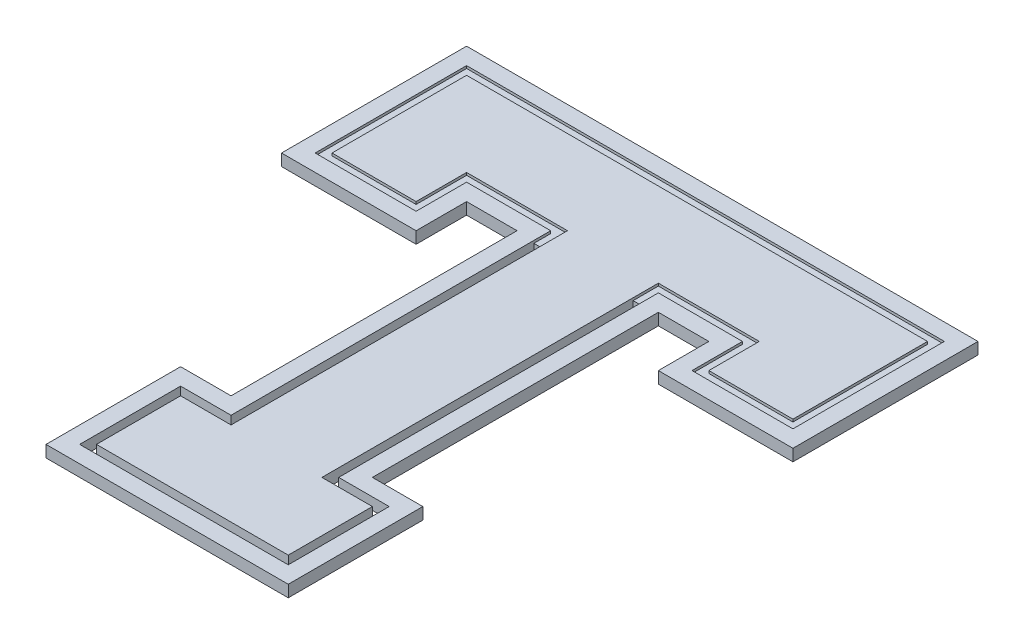
SolidWorks part; units mm, degrees
ref_plane "Front Plane" through (0, 0, 0) normal (0, 0, 1) x (1, 0, 0)
ref_plane "Top Plane" through (0, 0, 0) normal (0, 1, 0) x (1, 0, 0)
ref_plane "Right Plane" through (0, 0, 0) normal (1, 0, 0) x (0, 0, -1)
sketch "Sketch1" plane through (0, 0, 0) normal (0, 1, 0) x (1, 0, 0)
  line L0 (64.3712, 193.1137) -> (321.8562, 193.1137) construction
  line L1 (-20.32, 83.82) -> (-20.32, 55.88)
  line L2 (-20.32, 55.88) -> (0, 55.88)
  line L3 (0, 55.88) -> (0, 63.5)
  line L4 (0, 63.5) -> (7.62, 63.5)
  line L5 (7.62, 63.5) -> (7.62, 20.32)
  line L6 (7.62, 20.32) -> (0, 20.32)
  line L7 (0, 20.32) -> (0, 0)
  line L8 (0, 0) -> (36.576, 0)
  line L9 (36.576, 0) -> (36.576, 20.32)
  line L11 (36.576, 20.32) -> (28.956, 20.32)
  line L12 (28.956, 20.32) -> (28.956, 63.5)
  line L13 (28.956, 63.5) -> (36.576, 63.5)
  line L14 (36.576, 63.5) -> (36.576, 55.88)
  line L15 (36.576, 55.88) -> (56.896, 55.88)
  line L16 (56.896, 55.88) -> (56.896, 83.82)
  line L17 (56.896, 83.82) -> (-20.32, 83.82)
  line L19 (10.16, 17.78) -> (2.54, 17.78)
  line L20 (2.54, 17.78) -> (2.54, 2.54)
  line L21 (2.54, 2.54) -> (34.036, 2.54)
  line L22 (34.036, 2.54) -> (34.036, 17.78)
  line L23 (34.036, 17.78) -> (26.416, 17.78)
  line L24 (26.416, 17.78) -> (26.416, 63.5)
  line L35 (11.43, 16.51) -> (3.81, 16.51)
  line L36 (3.81, 16.51) -> (3.81, 3.81)
  line L37 (3.81, 3.81) -> (32.766, 3.81)
  line L38 (32.766, 3.81) -> (32.766, 16.51)
  line L39 (32.766, 16.51) -> (25.146, 16.51)
  line L40 (25.146, 16.51) -> (25.146, 63.5)
  line L50 (10.16, 63.5) -> (11.43, 63.5)
  line L51 (26.416, 63.5) -> (25.146, 63.5)
  line L52 (11.43, 63.5) -> (11.43, 16.51)
  line L53 (11.43, 67.31) -> (11.43, 16.51) construction
  line L54 (10.16, 63.5) -> (10.16, 17.78)
  line L55 (10.16, 66.04) -> (10.16, 17.78) construction
  line L57 (25.146, 16.51) -> (25.146, 67.31) construction
  line L59 (26.416, 17.78) -> (26.416, 66.04) construction
  line L60 (-17.78, 81.28) -> (-17.78, 58.42) construction
  line L61 (-16.51, 80.01) -> (-16.51, 59.69) construction
  line L62 (-17.78, 58.42) -> (-2.54, 58.42) construction
  line L63 (-16.51, 59.69) -> (-3.81, 59.69) construction
  line L64 (-2.54, 58.42) -> (-2.54, 66.04) construction
  line L65 (-3.81, 59.69) -> (-3.81, 67.31) construction
  line L66 (-3.81, 67.31) -> (11.43, 67.31) construction
  line L67 (-2.54, 66.04) -> (10.16, 66.04) construction
  line L68 (26.416, 66.04) -> (39.116, 66.04) construction
  line L69 (25.146, 67.31) -> (40.386, 67.31) construction
  line L70 (39.116, 66.04) -> (39.116, 58.42) construction
  line L71 (40.386, 67.31) -> (40.386, 59.69) construction
  line L72 (40.386, 59.69) -> (53.086, 59.69) construction
  line L73 (39.116, 58.42) -> (54.356, 58.42) construction
  line L74 (53.086, 59.69) -> (53.086, 80.01) construction
  line L75 (54.356, 58.42) -> (54.356, 81.28) construction
  line L76 (54.356, 81.28) -> (-17.78, 81.28) construction
  line L77 (53.086, 80.01) -> (-16.51, 80.01) construction
  point P54 (-6.6893, 80.4636)
  dimension "D1" = 27.94
  dimension "D2" = 20.32
  dimension "D3" = 20.32
  dimension "D4" = 7.62
  dimension "D5" = 7.62
  dimension "D6" = 7.62
  dimension "D7" = 7.62
  dimension "D8" = 27.94
  dimension "D9" = 43.18
  dimension "D10" = 43.18
  dimension "D11" = 7.62
  dimension "D12" = 20.32
  dimension "D13" = 36.576
  dimension "D14" = 7.62
  dimension "D15" = 2.54
  dimension "D16" = 3.81
extrude "Boss-Extrude1" add sketch "Sketch1" along normal blind 1.778
sketch "Sketch2" plane through (0, 1.778, 0) normal (0, 1, 0) x (1, 0, 0)
  line L0 (69.5522, 225.9617) -> (327.0372, 225.9617) construction
  line L1 (-20.32, 83.82) -> (-20.32, 55.88)
  line L2 (-20.32, 55.88) -> (0, 55.88)
  line L3 (0, 55.88) -> (0, 63.5)
  line L4 (0, 63.5) -> (7.62, 63.5)
  line L5 (7.62, 63.5) -> (7.62, 20.32)
  line L6 (7.62, 20.32) -> (0, 20.32)
  line L7 (0, 20.32) -> (0, 0)
  line L8 (0, 0) -> (36.576, 0)
  line L9 (36.576, 0) -> (36.576, 20.32)
  line L10 (36.576, 20.32) -> (28.956, 20.32)
  line L11 (28.956, 20.32) -> (28.956, 63.5)
  line L12 (28.956, 63.5) -> (36.576, 63.5)
  line L13 (36.576, 63.5) -> (36.576, 55.88)
  line L14 (36.576, 55.88) -> (56.896, 55.88)
  line L15 (56.896, 55.88) -> (56.896, 83.82)
  line L16 (56.896, 83.82) -> (-20.32, 83.82)
  line L33 (53.086, 80.01) -> (-16.51, 80.01)
  line L34 (-16.51, 80.01) -> (-16.51, 59.69)
  line L35 (-16.51, 59.69) -> (-3.81, 59.69)
  line L36 (-3.81, 59.69) -> (-3.81, 67.31)
  line L37 (-3.81, 67.31) -> (11.43, 67.31)
  line L38 (11.43, 67.31) -> (11.43, 16.51)
  line L39 (11.43, 16.51) -> (3.81, 16.51)
  line L40 (3.81, 16.51) -> (3.81, 3.81)
  line L41 (3.81, 3.81) -> (32.766, 3.81)
  line L42 (32.766, 3.81) -> (32.766, 16.51)
  line L43 (32.766, 16.51) -> (25.146, 16.51)
  line L44 (25.146, 16.51) -> (25.146, 67.31)
  line L45 (25.146, 67.31) -> (40.386, 67.31)
  line L46 (40.386, 67.31) -> (40.386, 59.69)
  line L47 (40.386, 59.69) -> (53.086, 59.69)
  line L48 (53.086, 59.69) -> (53.086, 80.01)
  line L49 (54.356, 81.28) -> (-17.78, 81.28)
  line L50 (-17.78, 81.28) -> (-17.78, 58.42)
  line L51 (-17.78, 58.42) -> (-2.54, 58.42)
  line L52 (-2.54, 58.42) -> (-2.54, 66.04)
  line L53 (-2.54, 66.04) -> (10.16, 66.04)
  line L54 (10.16, 66.04) -> (10.16, 17.78)
  line L55 (10.16, 17.78) -> (2.54, 17.78)
  line L56 (2.54, 17.78) -> (2.54, 2.54)
  line L57 (2.54, 2.54) -> (34.036, 2.54)
  line L58 (34.036, 2.54) -> (34.036, 17.78)
  line L59 (34.036, 17.78) -> (26.416, 17.78)
  line L60 (26.416, 17.78) -> (26.416, 66.04)
  line L61 (26.416, 66.04) -> (39.116, 66.04)
  line L62 (39.116, 66.04) -> (39.116, 58.42)
  line L63 (39.116, 58.42) -> (54.356, 58.42)
  line L64 (54.356, 58.42) -> (54.356, 81.28)
  line L65 (-20.32, 83.82) -> (-20.32, 55.88) construction
  line L66 (56.896, 83.82) -> (-20.32, 83.82) construction
  point P52 (0, 0)
  point P53 (0, 0)
  line M19 (10.16, 63.5) -> (11.43, 63.5)
  line M27 (25.146, 63.5) -> (26.416, 63.5)
  dimension "D3" = 142.1417
  dimension "D4" = 27.94
  dimension "D5" = 27.94
  dimension "D6" = 20.32
  dimension "D7" = 20.32
  dimension "D8" = 7.62
  dimension "D9" = 7.62
  dimension "D10" = 7.62
  dimension "D11" = 7.62
  dimension "D12" = 43.18
  dimension "D13" = 7.62
  dimension "D14" = 7.62
  dimension "D15" = 20.32
  dimension "D16" = 36.576
  dimension "D1" = 3.81
  dimension "D2" = 2.54
extrude "Cut-Extrude1" cut sketch "Sketch2" against normal blind 0.381 contours L63 L64 L49 L50 L51 L52 L53 L54 L38 L37 L36 L35 L34 L33 L48 L47 L46 L45 L44 L60 L61 L62 M19 M27
